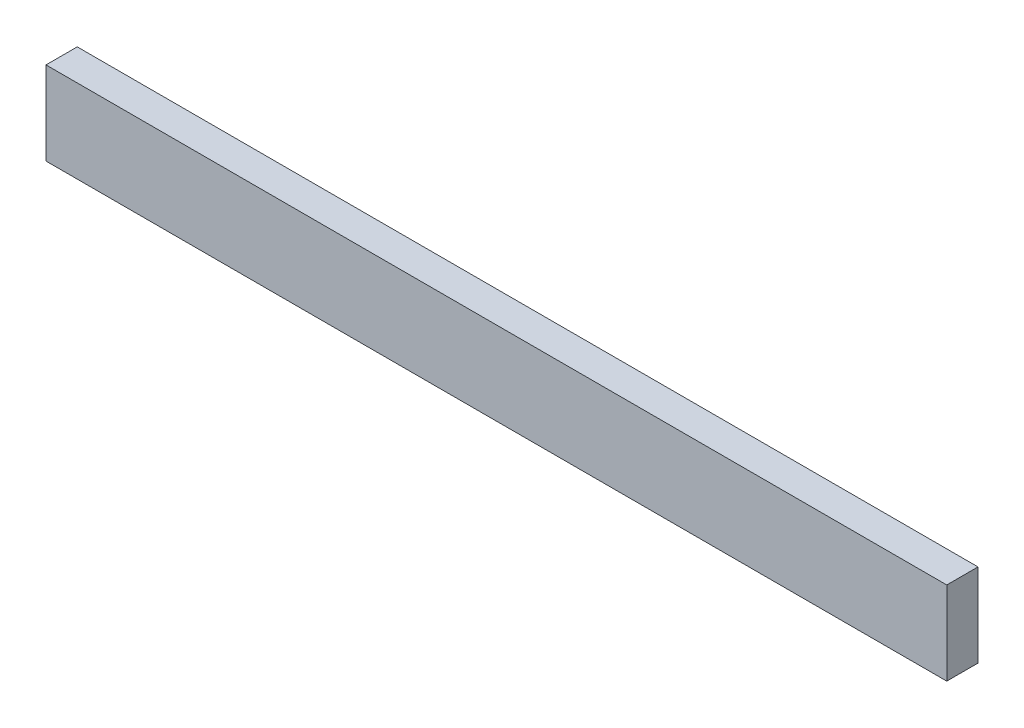
SolidWorks part; units mm, degrees
ref_plane "Plan de face" through (0, 0, 0) normal (0, 0, 1) x (1, 0, 0)
ref_plane "Plan de dessus" through (0, 0, 0) normal (0, 1, 0) x (1, 0, 0)
ref_plane "Plan de droite" through (0, 0, 0) normal (1, 0, 0) x (0, 0, -1)
sketch "Esquisse1" plane through (0, 0, 0) normal (0, 0, 1) x (1, 0, 0)
  line L1 (-417.4653, -469.4099) -> (15, -469.4099)
  line L2 (-417.4653, -469.4099) -> (-417.4653, -509.4099)
  line L3 (-417.4653, -509.4099) -> (15, -509.4099)
  line L4 (15, -469.4099) -> (15, -509.4099)
  line L7 (-30, -509.4099) -> (0, -509.4099) construction
  line L8 (15, -529.4099) -> (15, -469.4099) construction
extrude "Boss.-Extru.1" add sketch "Esquisse1" along normal blind 15
